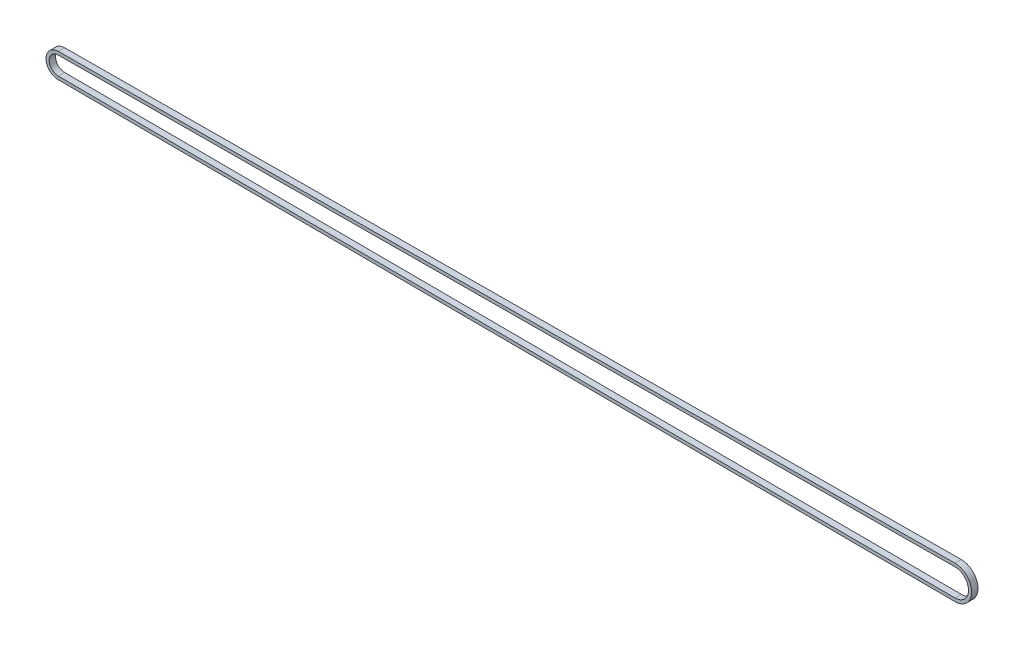
SolidWorks part; units mm, degrees
material "Rubber"
ref_plane "Front Plane" through (0, 0, 0) normal (0, 0, 1) x (1, 0, 0)
ref_plane "Top Plane" through (0, 0, 0) normal (0, 1, 0) x (1, 0, 0)
ref_plane "Right Plane" through (0, 0, 0) normal (1, 0, 0) x (0, 0, -1)
sketch "Sketch2" plane through (0, 0, 0) normal (0, 0, 1) x (1, 0, 0)
  line L0 (0, 0) -> (1, 0) construction
  line L1 (0, 0) -> (0, 1) construction
  line L2 (15.071, -72.6672) -> (-550.813, -70.3993)
  line L3 (-550.8262, -54.8995) -> (15.0531, -51.6675)
  arc A0 (15.0531, -51.6675) -> (15.071, -72.6672) centre (15.1131, -62.1673) cw
  arc A1 (-550.813, -70.3993) -> (-550.8262, -54.8995) centre (-550.7819, -62.6494) cw
extrude "Extrude-Thin1" add sketch "Sketch2" along normal blind 4 thin
